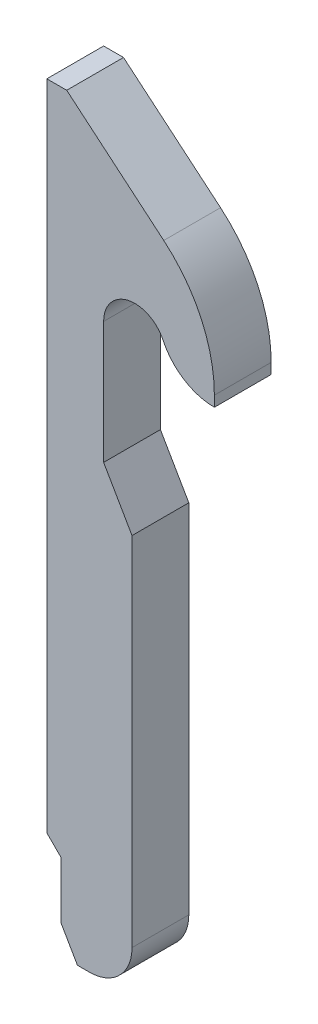
SolidWorks part; units mm, degrees
material "1.0553 (S355J0)"
ref_plane "Front Plane" through (0, 0, 0) normal (0, 0, 1) x (1, 0, 0)
ref_plane "Top Plane" through (0, 0, 0) normal (0, 1, 0) x (1, 0, 0)
ref_plane "Right Plane" through (0, 0, 0) normal (1, 0, 0) x (0, 0, -1)
sketch "Sketch1" plane through (0, 0, 0) normal (0, 0, 1) x (1, 0, 0)
  line L2 (5, 10) -> (10.7735, 0)
  line L3 (10.7735, 0) -> (15, 0)
  line L4 (30, 15) -> (30, 140.6795)
  line L5 (5, 10) -> (5, 30)
  line L6 (0, 0) -> (10.7735, 0) construction
  line L7 (30, 140.6795) -> (20, 158)
  line L8 (20, 158) -> (20, 201)
  line L18 (0, 265) -> (7, 265)
  line L19 (59, 198) -> (59, 194.3041)
  line L20 (41.1732, 236.2738) -> (7, 265)
  line L22 (0, 35) -> (0, 265)
  line L23 (0, 0) -> (0, 35) construction
  line L24 (0, 35) -> (5, 30)
  line L25 (0, 0) -> (10.7735, 0) construction
  arc A2 (15, 0) -> (30, 15) centre (15, 15) ccw
  arc A3 (40.9355, 205.7208) -> (20, 201) centre (31, 201) ccw
  arc A9 (41.1732, 236.2738) -> (59, 198) centre (9, 198) cw
  arc A11 (40.9355, 205.7208) -> (59, 194.3041) centre (59, 214.3041) ccw
  dimension "D4" = 45
  dimension "D6" = 265
  dimension "D8" = 15
  dimension "D5" = 11
  dimension "D7" = 50
  dimension "D13" = 7
  dimension "D14" = 43
  dimension "D16" = 30
  dimension "D10" = 20
  dimension "D2" = 10
  dimension "D3" = 35
  dimension "D9" = 5
  dimension "D11" = 30
  dimension "D12" = 3
  dimension "D15" = 30
  dimension "D17" = 64
  dimension "D18" = 30
  dimension "D19" = 59
  dimension "D20" = 20
  dimension "D21" = 5.7735
extrude "Boss-Extrude1" add sketch "Sketch1" along normal mid plane 20
